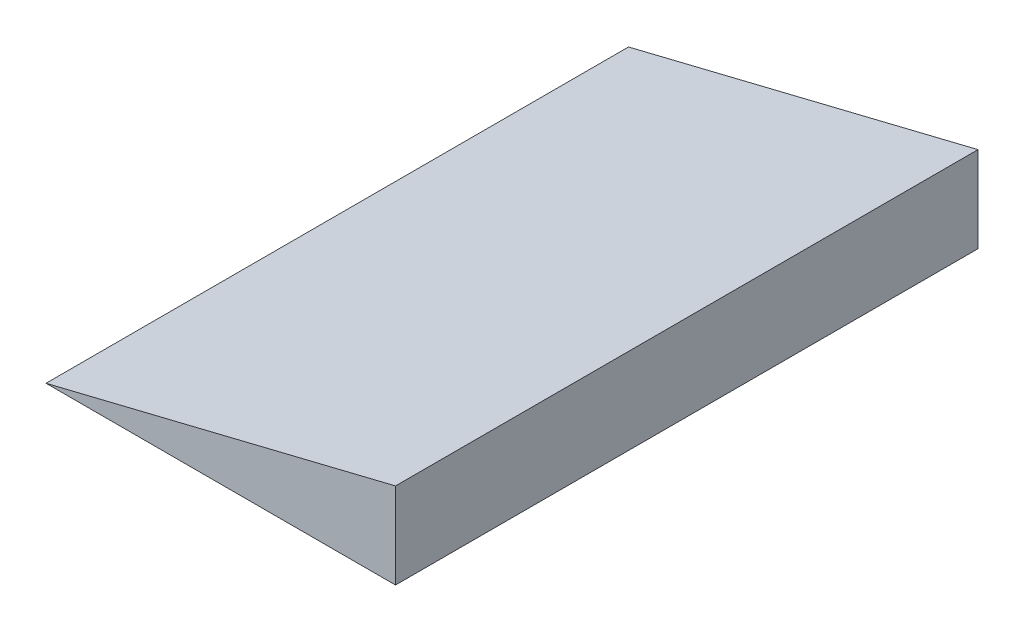
SolidWorks part; units mm, degrees
ref_plane "Front Plane" through (0, 0, 0) normal (0, 0, 1) x (1, 0, 0)
ref_plane "Top Plane" through (0, 0, 0) normal (0, 1, 0) x (1, 0, 0)
ref_plane "Right Plane" through (0, 0, 0) normal (1, 0, 0) x (0, 0, -1)
sketch "Sketch1" plane through (0, 0, 0) normal (0, 0, 1) x (1, 0, 0)
  line L0 (0, 0) -> (30, 0)
  line L1 (30, 0) -> (30, 7.3687)
  line L2 (30, 7.3687) -> (0, 0)
  dimension "D1" = 30
  dimension "D3" = 13.8
extrude "Boss-Extrude1" add sketch "Sketch1" along normal blind 50
